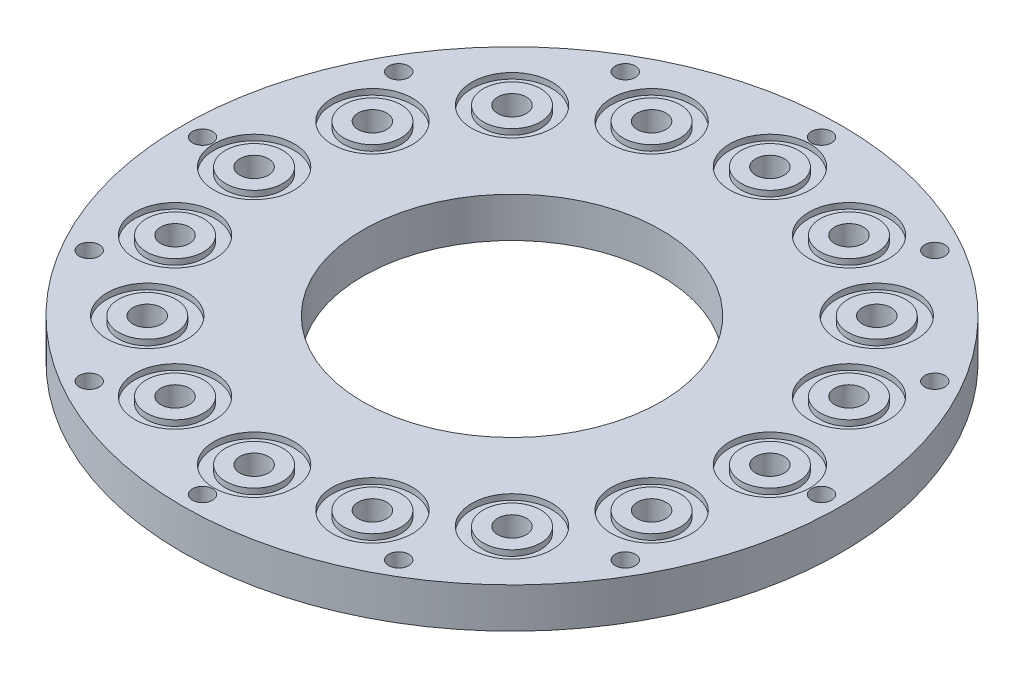
SolidWorks part; units mm, degrees
ref_plane "Front Plane" through (0, 0, 0) normal (0, 0, 1) x (1, 0, 0)
ref_plane "Top Plane" through (0, 0, 0) normal (0, 1, 0) x (1, 0, 0)
ref_plane "Right Plane" through (0, 0, 0) normal (1, 0, 0) x (0, 0, -1)
sketch "Sketch1" plane through (0, 0, 0) normal (0, 1, 0) x (1, 0, 0)
  circle A0 centre (0, 0) radius 57.5
  circle A1 centre (0, 0) radius 54 construction
  circle A2 centre (0, 54) radius 1.75
  circle A3 centre (27, 46.7654) radius 1.75
  circle A4 centre (46.7654, 27) radius 1.75
  circle A5 centre (54, 0) radius 1.75
  circle A6 centre (46.7654, -27) radius 1.75
  circle A7 centre (27, -46.7654) radius 1.75
  circle A8 centre (0, -54) radius 1.75
  circle A9 centre (-27, -46.7654) radius 1.75
  circle A10 centre (-46.7654, -27) radius 1.75
  circle A11 centre (-54, 0) radius 1.75
  circle A12 centre (-46.7654, 27) radius 1.75
  circle A13 centre (-27, 46.7654) radius 1.75
  circle A14 centre (0, 0) radius 26
  circle A15 centre (0, 0) radius 45 construction
  circle A16 centre (0, 45) radius 2.5
  circle A17 centre (17.2208, 41.5746) radius 2.5
  circle A18 centre (31.8198, 31.8198) radius 2.5
  circle A19 centre (41.5746, 17.2208) radius 2.5
  circle A20 centre (45, 0) radius 2.5
  circle A21 centre (41.5746, -17.2208) radius 2.5
  circle A22 centre (31.8198, -31.8198) radius 2.5
  circle A23 centre (17.2208, -41.5746) radius 2.5
  circle A24 centre (0, -45) radius 2.5
  circle A25 centre (-17.2208, -41.5746) radius 2.5
  circle A26 centre (-31.8198, -31.8198) radius 2.5
  circle A27 centre (-41.5746, -17.2208) radius 2.5
  circle A28 centre (-45, 0) radius 2.5
  circle A29 centre (-41.5746, 17.2208) radius 2.5
  circle A30 centre (-31.8198, 31.8198) radius 2.5
  circle A31 centre (-17.2208, 41.5746) radius 2.5
  point P31 (0, 0)
  point P55 (0, 0)
  dimension "D1" = 115
  dimension "D2" = 108
  dimension "D3" = 3.5
  dimension "D4" = 52
  dimension "D5" = 90
  dimension "D6" = 5
  dimension "D7" = 16
extrude "Boss-Extrude1" add sketch "Sketch1" along normal blind 7
sketch "Sketch2" plane through (0, 7, 0) normal (0, 1, 0) x (1, 0, 0)
  circle A0 centre (0, 0) radius 45 construction
  circle A1 centre (0, 45) radius 7
  circle A2 centre (17.2208, 41.5746) radius 7
  circle A3 centre (31.8198, 31.8198) radius 7
  circle A4 centre (41.5746, 17.2208) radius 7
  circle A5 centre (45, 0) radius 7
  circle A6 centre (41.5746, -17.2208) radius 7
  circle A7 centre (31.8198, -31.8198) radius 7
  circle A8 centre (17.2208, -41.5746) radius 7
  circle A9 centre (0, -45) radius 7
  circle A10 centre (-17.2208, -41.5746) radius 7
  circle A11 centre (-31.8198, -31.8198) radius 7
  circle A12 centre (0, 45) radius 5
  circle A13 centre (17.2208, 41.5746) radius 5
  circle A14 centre (31.8198, 31.8198) radius 5
  circle A15 centre (41.5746, 17.2208) radius 5
  circle A16 centre (45, 0) radius 5
  circle A17 centre (41.5746, -17.2208) radius 5
  circle A18 centre (31.8198, -31.8198) radius 5
  circle A19 centre (17.2208, -41.5746) radius 5
  circle A20 centre (0, -45) radius 5
  circle A21 centre (-17.2208, -41.5746) radius 5
  circle A22 centre (-31.8198, -31.8198) radius 5
  circle A23 centre (-41.5746, -17.2208) radius 5
  circle A24 centre (-45, 0) radius 5
  circle A25 centre (-41.5746, 17.2208) radius 5
  circle A26 centre (-31.8198, 31.8198) radius 5
  circle A27 centre (-17.2208, 41.5746) radius 5
  circle A28 centre (-41.5746, -17.2208) radius 7
  circle A29 centre (-45, 0) radius 7
  circle A30 centre (-41.5746, 17.2208) radius 7
  circle A31 centre (-31.8198, 31.8198) radius 7
  circle A32 centre (-17.2208, 41.5746) radius 7
  point P28 (0, 0)
  point P51 (0, 0)
  dimension "D1" = 14
  dimension "D3" = 10
  dimension "D2" = 16
  dimension "D4" = 16
extrude "Cut-Extrude1" cut sketch "Sketch2" against normal blind 1
